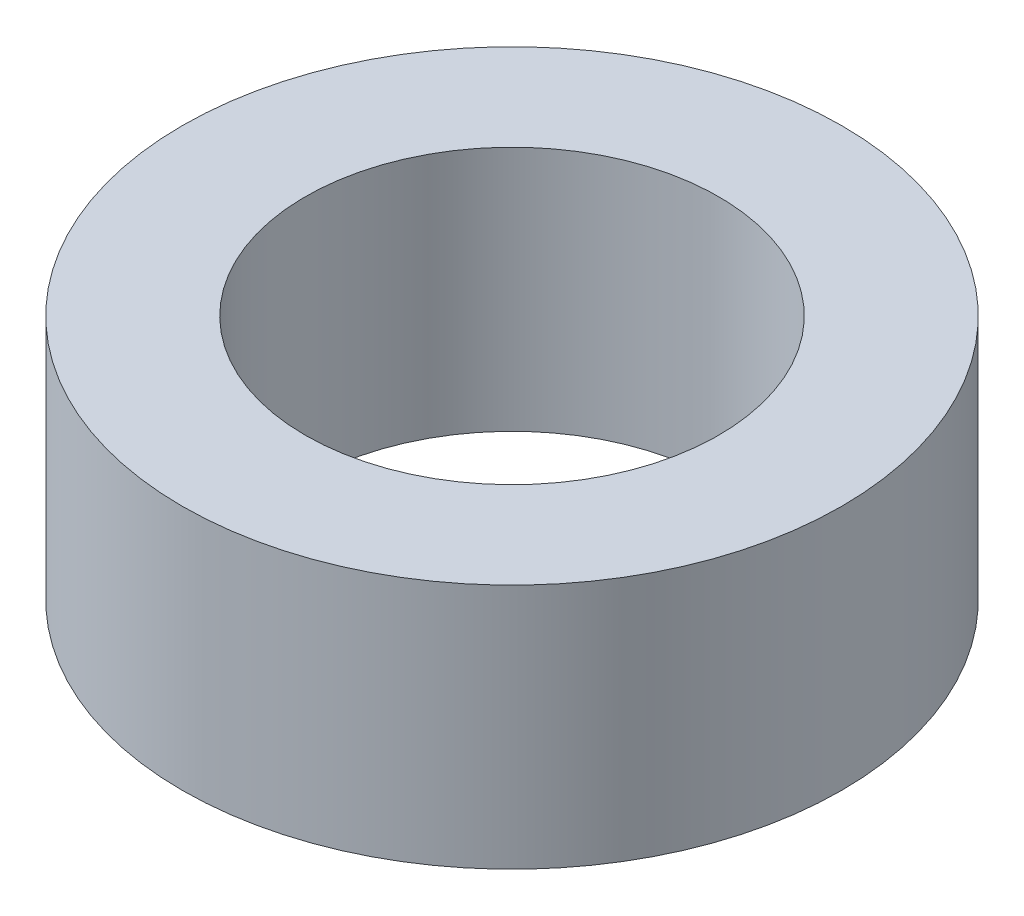
SolidWorks part; units mm, degrees
ref_plane "Front Plane" through (0, 0, 0) normal (0, 0, 1) x (1, 0, 0)
ref_plane "Top Plane" through (0, 0, 0) normal (0, 1, 0) x (1, 0, 0)
ref_plane "Right Plane" through (0, 0, 0) normal (1, 0, 0) x (0, 0, -1)
sketch "Sketch1" plane through (0, 0, 0) normal (0, 1, 0) x (1, 0, 0)
  circle A0 centre (0, 0) radius 2.1
  circle A1 centre (0, 0) radius 3.35
  dimension "D1" = 4.2
  dimension "D2" = 6.7
extrude "Boss-Extrude1" add sketch "Sketch1" along normal blind 2.5
